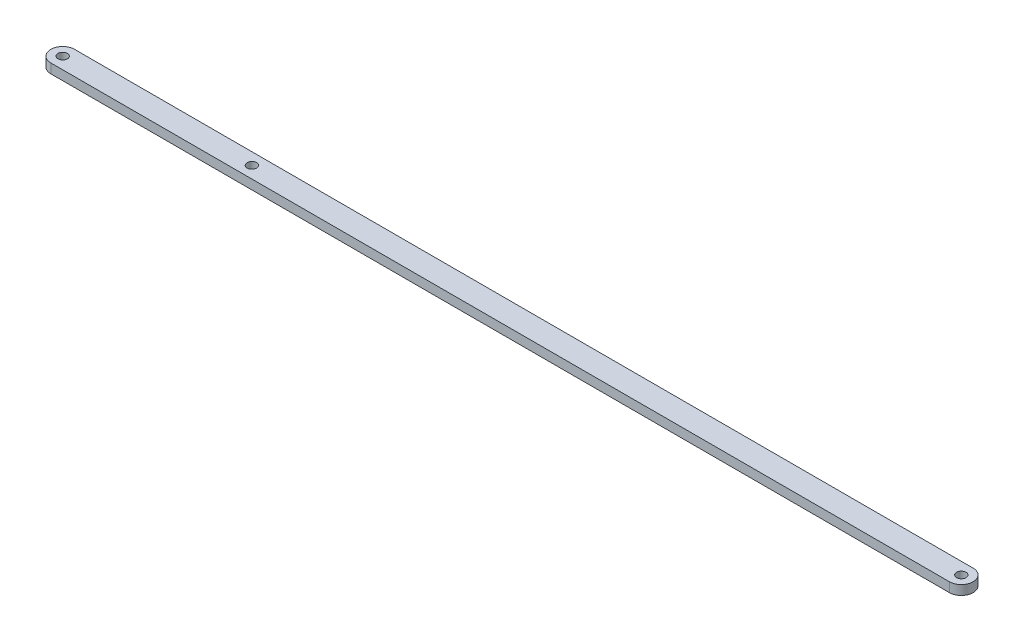
SolidWorks part; units mm, degrees
ref_plane "Front Plane" through (0, 0, 0) normal (0, 0, 1) x (1, 0, 0)
ref_plane "Top Plane" through (0, 0, 0) normal (0, 1, 0) x (1, 0, 0)
ref_plane "Right Plane" through (0, 0, 0) normal (1, 0, 0) x (0, 0, -1)
sketch "Sketch1" plane through (0, 0, 0) normal (0, 1, 0) x (1, 0, 0)
  line L0 (-10, 0) -> (180, 0) construction
  line L1 (-10, 2.5) -> (180, 2.5)
  line L2 (-10, -2.5) -> (180, -2.5)
  arc A0 (-10, 2.5) -> (-10, -2.5) centre (-10, 0) ccw
  arc A1 (180, -2.5) -> (180, 2.5) centre (180, 0) ccw
  circle A2 centre (180, 0) radius 1
  circle A3 centre (-10, 0) radius 1
  point P3 (85, 0)
  dimension "D3" = 2
  dimension "D4" = 2.5
  dimension "D5" = 2
  dimension "D1" = 190
  dimension "D12" = 10
extrude "Boss-Extrude1" add sketch "Sketch1" along normal blind 2
sketch "Sketch2" plane through (0, 2, 0) normal (0, 1, 0) x (1, 0, 0)
  line L0 (-10, 0) -> (30, 0) construction
  line L1 (-10, 2.5) -> (30, 2.5)
  line L2 (-10, -2.5) -> (30, -2.5)
  arc A0 (-10, 2.5) -> (-10, -2.5) centre (-10, 0) ccw
  arc A1 (30, -2.5) -> (30, 2.5) centre (30, 0) ccw
  circle A2 centre (30, 0) radius 1
  point P4 (10, 0)
  dimension "D1" = 20
extrude "Cut-Extrude1" cut sketch "Sketch2" against normal through all contours A2
